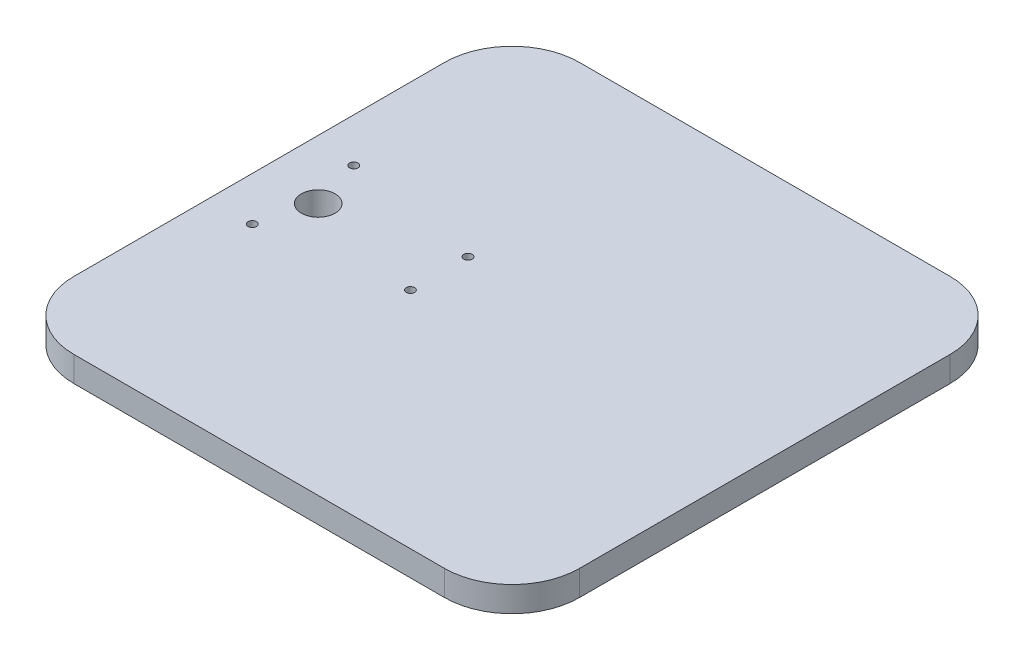
SolidWorks part; units mm, degrees
ref_plane "Front Plane" through (0, 0, 0) normal (0, 0, 1) x (1, 0, 0)
ref_plane "Top Plane" through (0, 0, 0) normal (0, 1, 0) x (1, 0, 0)
ref_plane "Right Plane" through (0, 0, 0) normal (1, 0, 0) x (0, 0, -1)
sketch "Sketch1" plane through (0, 0, 0) normal (0, 1, 0) x (1, 0, 0)
  line L1 (75, -75) -> (-75, -75)
  line L2 (75, -75) -> (75, 75)
  line L3 (75, 75) -> (-75, 75)
  line L4 (-75, -75) -> (-75, 75)
  line L5 (75, -75) -> (-75, 75) construction
  line L6 (75, 75) -> (-75, -75) construction
  point P0 (0, 0)
  dimension "D1" = 150
  dimension "D2" = 150
extrude "Boss-Extrude1" add sketch "Sketch1" along normal blind 7.5
sketch "Sketch2" plane through (0, 7.5, 0) normal (0, 1, 0) x (1, 0, 0)
  line L0 (-20.9607, 0) -> (-66.5864, 0) construction
  circle A0 centre (-61.9857, -15.05) radius 1.25
  circle A1 centre (-61.9857, 15.05) radius 1.25
  circle A2 centre (-21.5857, 8.55) radius 1.25
  circle A3 centre (-21.5857, -8.55) radius 1.25
  circle A4 centre (-57.4857, 0) radius 5
  dimension "D1" = 2.5
  dimension "D4" = 2.5
  dimension "D5" = 2.5
  dimension "D8" = 10
  dimension "D2" = 15.05
  dimension "D3" = 15.05
  dimension "D6" = 8.55
  dimension "D7" = 40.4
  dimension "D9" = 4.5
extrude "Cut-Extrude1" cut sketch "Sketch2" against normal through all both and the other way through all
fillet "Fillet1" radius 20 4 edges at (75, 3.75, -75) (75, 3.75, 75) (-75, 3.75, 75) (-75, 3.75, -75)
